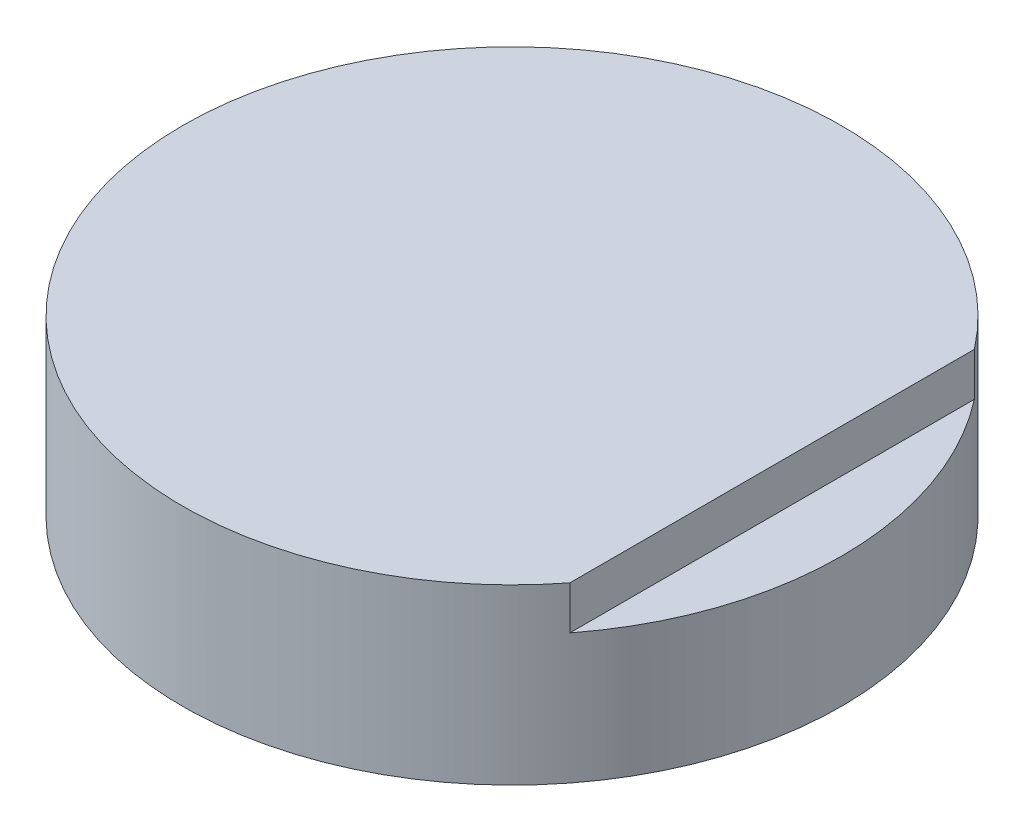
SolidWorks part; units mm, degrees
other "Fixed Steel Cup Liner 1"
ref_plane "Front Plane" through (0, 0, 0) normal (0, 0, 1) x (1, 0, 0)
ref_plane "Top Plane" through (0, 0, 0) normal (0, 1, 0) x (1, 0, 0)
ref_plane "Right Plane" through (0, 0, 0) normal (1, 0, 0) x (0, 0, -1)
sketch3d "Keyed Back Sketch datum points"
  point P0 (-56.2917, -69, 0)
  point P1 (-46.2917, -69, 0)
  point P2 (-56.2917, -69, 10)
ref_plane "Keyed Back Sketch plane" through (0, -69, 0) normal (0, -1, 0) x (-1, 0, 0)
sketch "Keyed Back Sketch" plane through (0, -69, 0) normal (0, -1, 0) x (-1, 0, 0)
  line L0 (23.2917, 2.3324) -> (23.2917, -2.3324)
  arc A0 (23.2917, -2.3324) -> (23.2917, 2.3324) centre (26.2917, 0) ccw
extrude "Keyed Back" add sketch "Keyed Back Sketch" along normal blind 0.5 separate body
sketch3d "Cup Blank Sketch datum points"
  point P0 (-56.2917, -69.5, 0)
  point P1 (-46.2917, -69.5, 0)
  point P2 (-56.2917, -69.5, 10)
ref_plane "Cup Blank Sketch plane" through (0, -69.5, 0) normal (0, -1, 0) x (-1, 0, 0)
sketch "Cup Blank Sketch" plane through (0, -69.5, 0) normal (0, -1, 0) x (-1, 0, 0)
  circle A0 centre (26.2917, 0) radius 3.8
extrude "Cup Blank" add sketch "Cup Blank Sketch" along normal blind 1.5
sketch3d "Spherical Bearing Seat axis line"
  line L0 (-26.2917, -73, -10) -> (-26.2917, -73, 10) construction
ref_axis "Spherical Bearing Seat axis" through (-26.2917, -73, -10) along (0, 0, 1)
sketch3d "Spherical Bearing Seat profile datum points"
  point P0 (-26.2917, -73, 0)
  point P1 (-16.2917, -73, 0)
  point P2 (-26.2917, -73, 10)
ref_plane "Spherical Bearing Seat profile plane" through (0, -73, 0) normal (0, -1, 0) x (-1, 0, 0)
sketch "Spherical Bearing Seat profile" plane through (0, -73, 0) normal (0, -1, 0) x (-1, 0, 0)
  line L0 (26.2917, -3.1) -> (26.2917, 3.1)
  arc A0 (26.2917, 3.1) -> (26.2917, -3.1) centre (26.2917, 0) ccw
revolve "Spherical Bearing Seat" cut sketch "Spherical Bearing Seat profile" angle 360 about axis through (-26.2917, -73, -10) along (0, 0, 1)
